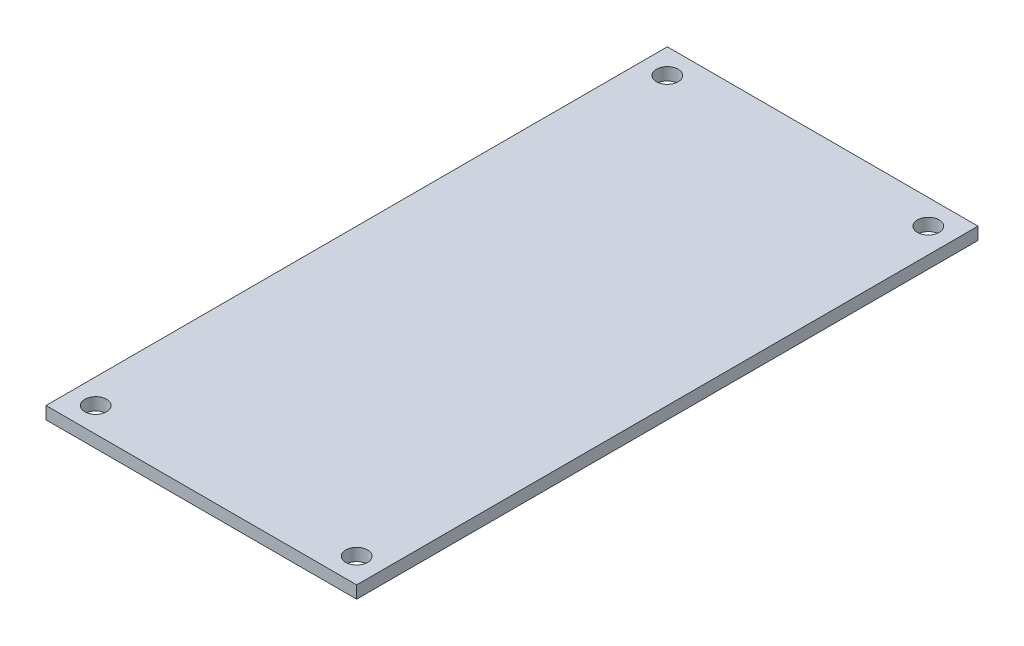
SolidWorks part; units mm, degrees
ref_plane "정면" through (0, 0, 0) normal (0, 0, 1) x (1, 0, 0)
ref_plane "윗면" through (0, 0, 0) normal (0, 1, 0) x (1, 0, 0)
ref_plane "우측면" through (0, 0, 0) normal (1, 0, 0) x (0, 0, -1)
sketch "스케치1" plane through (0, 0, 0) normal (0, 1, 0) x (1, 0, 0)
  line L0 (0, 50) -> (0, -50) construction
  line L5 (25, -50) -> (-25, -50)
  line L6 (25, -50) -> (25, 50)
  line L7 (25, 50) -> (-25, 50)
  line L8 (-25, -50) -> (-25, 50)
  line L9 (25, -50) -> (-25, 50) construction
  line L10 (25, 50) -> (-25, -50) construction
  line L11 (-25, 0) -> (25, 0) construction
  circle A0 centre (-21, 46) radius 1.75
  circle A1 centre (21, 46) radius 1.75
  circle A2 centre (21, -46) radius 1.75
  circle A3 centre (-21, -46) radius 1.75
  point P0 (0, 0)
  dimension "D3" = 3.5
  dimension "D1" = 50
  dimension "D2" = 100
  dimension "D4" = 4
  dimension "D5" = 4
extrude "보스-돌출1" add sketch "스케치1" along normal blind 2
ref_plane "평면1" through (-21, 0, 0) normal (1, 0, 0) x (0, 0, -1)
